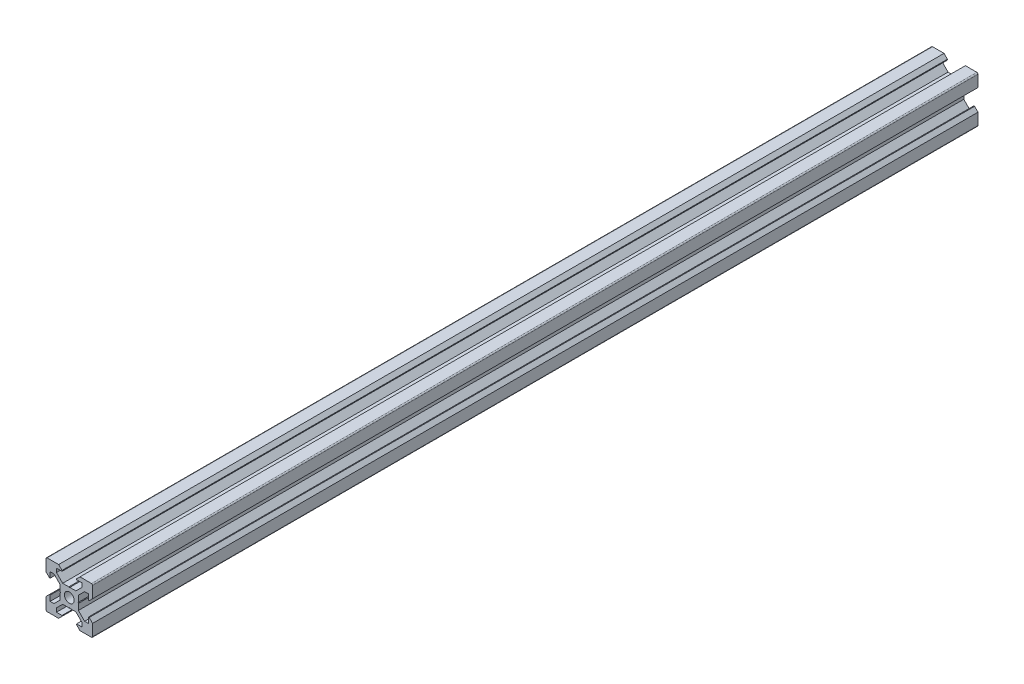
SolidWorks part; units mm, degrees
material "6061-T6 (SS)"
ref_plane "Front Plane" through (0, 0, 0) normal (0, 0, 1) x (1, 0, 0)
ref_plane "Top Plane" through (0, 0, 0) normal (0, 1, 0) x (1, 0, 0)
ref_plane "Right Plane" through (0, 0, 0) normal (1, 0, 0) x (0, 0, -1)
sketch "Sketch1" plane through (0, 0, 0) normal (0, 0, 1) x (1, 0, 0)
  line L1 (9.5, -10) -> (-9.5, -10)
  line L2 (10, -9.5) -> (10, 9.5)
  line L3 (9.5, 10) -> (-9.5, 10)
  line L4 (-10, -9.5) -> (-10, 9.5)
  line L5 (10, -10) -> (-10, 10) construction
  line L6 (10, 10) -> (-10, -10) construction
  circle A0 centre (0, 0) radius 2.1
  arc A1 (-9.5, 10) -> (-10, 9.5) centre (-9.5, 9.5) ccw
  arc A2 (10, 9.5) -> (9.5, 10) centre (9.5, 9.5) ccw
  arc A3 (9.5, -10) -> (10, -9.5) centre (9.5, -9.5) ccw
  arc A4 (-9.5, -10) -> (-10, -9.5) centre (-9.5, -9.5) cw
  point P0 (0, 0)
  line B0 (0, 0) -> (0, 10) construction
  line B1 (0, 3.69) -> (-0.21, 3.9)
  line B2 (-0.21, 3.9) -> (-2.8393, 3.9)
  line B3 (-2.8393, 3.9) -> (-5.5, 6.5607)
  line B4 (-5.5, 6.5607) -> (-5.5, 8.2)
  line B5 (-5.5, 8.2) -> (-3.125, 8.2)
  line B6 (-3.125, 8.2) -> (-3.125, 8.545)
  line B7 (-3.125, 8.545) -> (-4.58, 10)
  line B8 (-4.58, 10) -> (4.58, 10)
  line B9 (0, 0) -> (-5.9132, 5.9132) construction
  line B10 (3.125, 8.545) -> (4.58, 10)
  line B11 (3.125, 8.2) -> (3.125, 8.545)
  line B12 (5.5, 8.2) -> (3.125, 8.2)
  line B13 (5.5, 6.5607) -> (5.5, 8.2)
  line B14 (2.8393, 3.9) -> (5.5, 6.5607)
  line B15 (0.21, 3.9) -> (2.8393, 3.9)
  line B16 (0, 3.69) -> (0.21, 3.9)
  line B17 (0, 0) -> (-10, 0) construction
  line B18 (-3.69, 0) -> (-3.9, -0.21)
  line B19 (-3.9, -0.21) -> (-3.9, -2.8393)
  line B20 (-3.9, -2.8393) -> (-6.5607, -5.5)
  line B21 (-6.5607, -5.5) -> (-8.2, -5.5)
  line B22 (-8.2, -5.5) -> (-8.2, -3.125)
  line B23 (-8.2, -3.125) -> (-8.545, -3.125)
  line B24 (-8.545, -3.125) -> (-10, -4.58)
  line B25 (-10, -4.58) -> (-10, 4.58)
  line B26 (0, 0) -> (-5.9132, -5.9132) construction
  line B27 (-8.545, 3.125) -> (-10, 4.58)
  line B28 (-8.2, 3.125) -> (-8.545, 3.125)
  line B29 (-8.2, 5.5) -> (-8.2, 3.125)
  line B30 (-6.5607, 5.5) -> (-8.2, 5.5)
  line B31 (-3.9, 2.8393) -> (-6.5607, 5.5)
  line B32 (-3.9, 0.21) -> (-3.9, 2.8393)
  line B33 (-3.69, 0) -> (-3.9, 0.21)
  line B34 (0, 0) -> (0, -10) construction
  line B35 (0, -3.69) -> (0.21, -3.9)
  line B36 (0.21, -3.9) -> (2.8393, -3.9)
  line B37 (2.8393, -3.9) -> (5.5, -6.5607)
  line B38 (5.5, -6.5607) -> (5.5, -8.2)
  line B39 (5.5, -8.2) -> (3.125, -8.2)
  line B40 (3.125, -8.2) -> (3.125, -8.545)
  line B41 (3.125, -8.545) -> (4.58, -10)
  line B42 (4.58, -10) -> (-4.58, -10)
  line B43 (0, 0) -> (5.9132, -5.9132) construction
  line B44 (-3.125, -8.545) -> (-4.58, -10)
  line B45 (-3.125, -8.2) -> (-3.125, -8.545)
  line B46 (-5.5, -8.2) -> (-3.125, -8.2)
  line B47 (-5.5, -6.5607) -> (-5.5, -8.2)
  line B48 (-2.8393, -3.9) -> (-5.5, -6.5607)
  line B49 (-0.21, -3.9) -> (-2.8393, -3.9)
  line B50 (0, -3.69) -> (-0.21, -3.9)
  line B51 (0, 0) -> (10, 0) construction
  line B52 (3.69, 0) -> (3.9, 0.21)
  line B53 (3.9, 0.21) -> (3.9, 2.8393)
  line B54 (3.9, 2.8393) -> (6.5607, 5.5)
  line B55 (6.5607, 5.5) -> (8.2, 5.5)
  line B56 (8.2, 5.5) -> (8.2, 3.125)
  line B57 (8.2, 3.125) -> (8.545, 3.125)
  line B58 (8.545, 3.125) -> (10, 4.58)
  line B59 (10, 4.58) -> (10, -4.58)
  line B60 (0, 0) -> (5.9132, 5.9132) construction
  line B61 (8.545, -3.125) -> (10, -4.58)
  line B62 (8.2, -3.125) -> (8.545, -3.125)
  line B63 (8.2, -5.5) -> (8.2, -3.125)
  line B64 (6.5607, -5.5) -> (8.2, -5.5)
  line B65 (3.9, -2.8393) -> (6.5607, -5.5)
  line B66 (3.9, -0.21) -> (3.9, -2.8393)
  line B67 (3.69, 0) -> (3.9, -0.21)
  dimension "D1" = 4.2
  dimension "D3" = 0.5
  dimension "D2" = 20
sketch_block_instance "V Slot 1-4"
sketch_block "V Slot 1" parameters "D1"=10, "D2"=11, "D3"=4.3, "D4"=1.8, "D5"=0.21, "D6"=45, "D7"=9.16, "D8"=1.5, "D9"=6.25
sketch_block_instance "V Slot 1-5"
sketch_block_instance "V Slot 1-6"
sketch_block_instance "V Slot 1-7"
extrude "Boss-Extrude1" add sketch "Sketch1" along normal blind 380 contours B67 B52 B53 B54 B55 B56 B57 B58 L2 A2 L3 B10 B11 B12 B13 B14 B15 B16 B1 B2 B3 B4 B5 B6 B7 A1 L4 B27 B28 B29 B30 B31 B32 B33 B18 B19 B20 B21 B22 B23 B24 A4 L1 B44 B45 B46 B47 B48 B49
